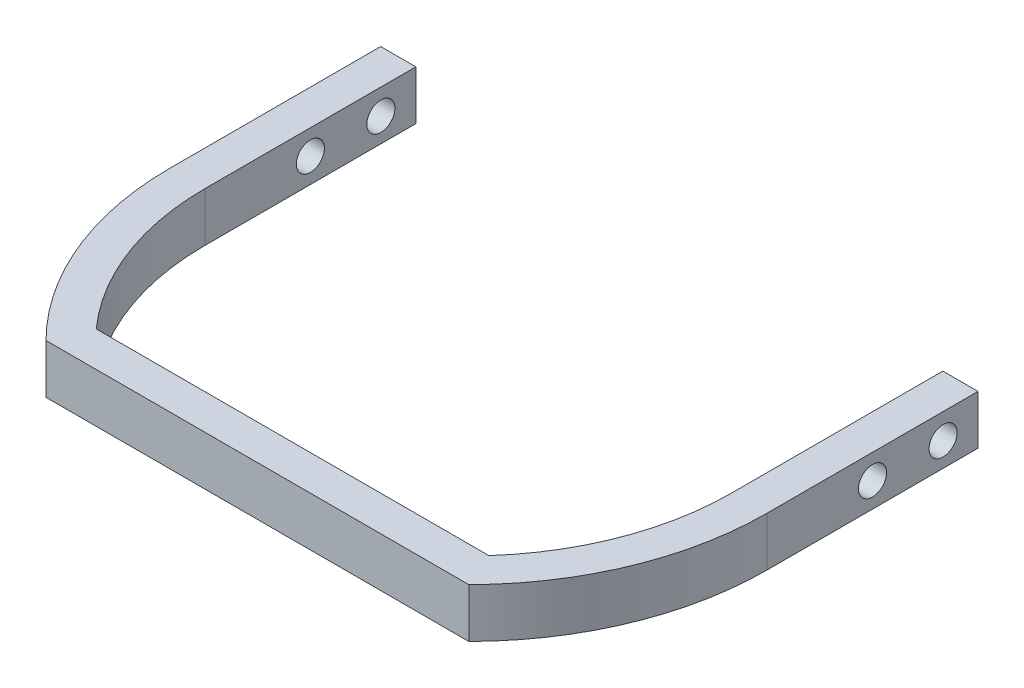
SolidWorks part; units mm, degrees
ref_plane "Front" through (0, 0, 0) normal (0, 0, 1) x (1, 0, 0)
ref_plane "Top" through (0, 0, 0) normal (0, 1, 0) x (1, 0, 0)
ref_plane "Right" through (0, 0, 0) normal (1, 0, 0) x (0, 0, -1)
sketch "Эскиз1" plane through (0, 0, 0) normal (0, 1, 0) x (1, 0, 0)
  line L0 (0, 40.2802) -> (0, -37.694) construction
  line L1 (-42.47, 30) -> (-37.47, 30)
  line L2 (-42.47, 30) -> (-42.47, 0)
  line L3 (-42.47, 0) -> (-37.47, 0)
  line L4 (-37.47, 30) -> (-37.47, 0)
  line L5 (37.47, 30) -> (42.47, 30)
  line L6 (37.47, 30) -> (37.47, 0)
  line L7 (37.47, 0) -> (42.47, 0)
  line L8 (42.47, 30) -> (42.47, 0)
  dimension "D1" = 30
  dimension "D2" = 5
  dimension "D3" = 84.94
extrude "Бобышка-Вытянуть1" add sketch "Эскиз1" along normal blind 7
sketch "Эскиз2" plane through (-42.47, 0, 0) normal (-1, 0, 0) x (0, 0, 1)
  circle A0 centre (-15, 3.5) radius 2
  circle A1 centre (-25.0331, 3.4071) radius 2
  dimension "D1" = 4
extrude "Вырез-Вытянуть1" cut sketch "Эскиз2" against normal through all
sketch "Эскиз3" plane through (0, 7, 0) normal (0, 1, 0) x (1, 0, 0)
  line L0 (27.9106, -25) -> (-27.9106, -25)
  line L1 (30.0616, -30) -> (-30.0616, -30)
  line L2 (42.47, 0) -> (37.47, 0)
  line L3 (-37.47, 0) -> (-42.47, 0)
  circle A0 centre (0, 0) radius 37.47
  circle A1 centre (0, 0) radius 42.47
  point P2 (37.47, 0)
  point P3 (-37.47, 0)
  point P8 (42.47, 0)
  point P9 (-42.47, 0)
  line M4 (-42.47, 0) -> (-37.47, 0)
  dimension "D1" = 5
  dimension "D2" = 25
extrude "Бобышка-Вытянуть2" add sketch "Эскиз3" against normal blind 7 contours L1 A0 L0 | A1 L1 A0 M4 | L1 A1 L2 A0
